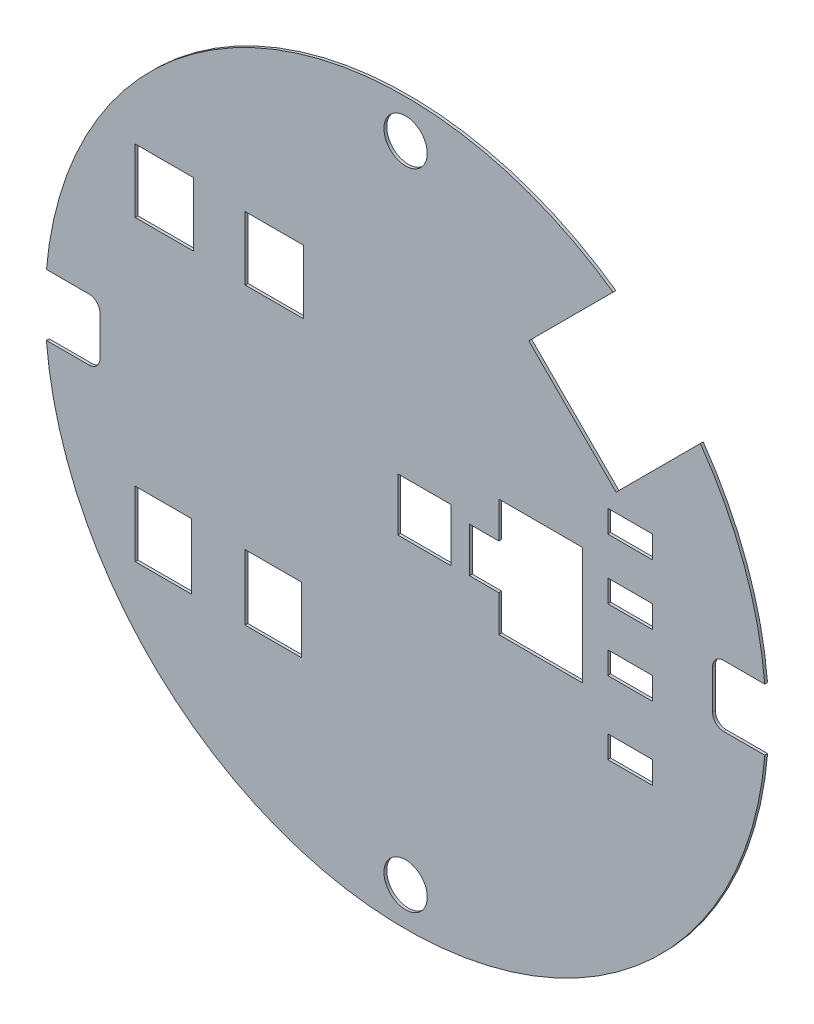
SolidWorks part; units mm, degrees
material "EPDM"
ref_plane "前视基准面" through (0, 0, 0) normal (0, 0, 1) x (1, 0, 0)
ref_plane "上视基准面" through (0, 0, 0) normal (0, 1, 0) x (1, 0, 0)
ref_plane "右视基准面" through (0, 0, 0) normal (1, 0, 0) x (0, 0, -1)
ref_plane "基准面1" through (0, 0, -54.804) normal (0, 0, -1) x (-1, 0, 0)
sketch "草图1" plane through (0, 0, -54.804) normal (0, 0, -1) x (-1, 0, 0)
  circle A0 centre (24.6985, -1.5122) radius 25.8011
  circle A1 centre (24.6985, 21.5378) radius 1.55
  circle A2 centre (24.6985, -24.5622) radius 1.55
extrude "凸台-拉伸1" add sketch "草图1" along normal blind 0.2 from surface
sketch "草图2" plane through (0, 0, -54.804) normal (0, 0, -1) x (-1, 0, 0)
  line L0 (21.4655, 0.6268) -> (25.2595, 0.6268)
  line L9 (32.0065, 11.4219) -> (36.1815, 11.4219)
  line L18 (36.1815, 11.4219) -> (36.1815, 6.8659)
  line L19 (32.0065, 6.8659) -> (36.1815, 6.8659)
  line L20 (32.0065, 11.4219) -> (32.0065, 6.8659)
  line L21 (39.8805, 11.6758) -> (44.0555, 11.6758)
  line L22 (44.0555, 11.6758) -> (44.0555, 7.1198)
  line L23 (39.8805, 7.1198) -> (44.0555, 7.1198)
  line L24 (39.8805, 11.6758) -> (39.8805, 7.1198)
  line L25 (32.1335, -9.5332) -> (36.1815, -9.5332)
  line L26 (36.1815, -9.5332) -> (36.1815, -14.2162)
  line L27 (32.1335, -14.2162) -> (36.1815, -14.2162)
  line L28 (32.1335, -9.5332) -> (32.1335, -14.2162)
  line L29 (40.0075, -9.5332) -> (44.0555, -9.5332)
  line L30 (44.0555, -9.5332) -> (44.0555, -14.2162)
  line L31 (40.0075, -14.2162) -> (44.0555, -14.2162)
  line L32 (40.0075, -9.5332) -> (40.0075, -14.2162)
  line L37 (25.2595, 0.6268) -> (25.2595, -3.1672)
  line L38 (21.4655, -3.1672) -> (25.2595, -3.1672)
  line L39 (21.4655, 0.6268) -> (21.4655, -3.1672)
extrude "切除-拉伸1" cut sketch "草图2" against normal up to next from surface
sketch "草图3" plane through (0, 0, -54.804) normal (0, 0, -1) x (-1, 0, 0)
  line L4 (15.8822, 13.5563) -> (9.6314, 7.3055)
  line L5 (9.6314, 7.3055) -> (2.9964, 13.9404)
  line L6 (2.9964, 13.9404) -> (9.2472, 20.1913)
  line L7 (9.2472, 20.1913) -> (15.8822, 13.5563)
extrude "切除-拉伸2" cut sketch "草图3" against normal up to next from surface
sketch "草图4" plane through (0, 0, -54.804) normal (0, 0, -1) x (-1, 0, 0)
  line L0 (7.0304, 4.4068) -> (7.0304, 6.0068)
  line L3 (7.0304, 6.0068) -> (10.2304, 6.0068)
  line L4 (10.2304, 6.0068) -> (10.2304, 4.4068)
  line L5 (8.6304, 4.4068) -> (7.0304, 4.4068)
  line L6 (8.6304, 4.4068) -> (10.2304, 4.4068)
  line L7 (7.0304, 0.0868) -> (7.0304, 1.6868)
  line L8 (7.0304, 1.6868) -> (10.2304, 1.6868)
  line L9 (10.2304, 1.6868) -> (10.2304, 0.0868)
  line L10 (8.6304, 0.0868) -> (7.0304, 0.0868)
  line L11 (8.6304, 0.0868) -> (10.2304, 0.0868)
  line L12 (7.0304, -4.3632) -> (7.0304, -2.7632)
  line L13 (7.0304, -2.7632) -> (10.2304, -2.7632)
  line L14 (10.2304, -2.7632) -> (10.2304, -4.3632)
  line L15 (8.6304, -4.3632) -> (7.0304, -4.3632)
  line L16 (8.6304, -4.3632) -> (10.2304, -4.3632)
  line L17 (7.0304, -9.5732) -> (7.0304, -7.9732)
  line L18 (7.0304, -7.9732) -> (10.2304, -7.9732)
  line L19 (10.2304, -7.9732) -> (10.2304, -9.5732)
  line L20 (8.6304, -9.5732) -> (7.0304, -9.5732)
  line L21 (8.6304, -9.5732) -> (10.2304, -9.5732)
  dimension "D1" = 2
  dimension "D2" = 2
  dimension "D3" = 2
extrude "切除-拉伸3" cut sketch "草图4" against normal up to next from surface
sketch "草图5" plane through (0, 0, -54.804) normal (0, 0, -1) x (-1, 0, 0)
  line L1 (14.8535, 2.6759) -> (12.0535, 2.6759)
  line L5 (14.8535, -5.7241) -> (12.0535, -5.7241)
  line L6 (12.0535, -5.7241) -> (12.0535, 2.6759)
  line L7 (14.8535, 2.6759) -> (17.6535, 2.6759)
  line L8 (20.1285, -3.1241) -> (18.0285, -3.1241)
  line L10 (17.6535, 2.6759) -> (18.0285, 2.6759)
  line L11 (18.0285, 2.6759) -> (18.0285, 0.0759)
  line L12 (18.0285, -3.1241) -> (18.0285, -5.7241)
  line L13 (18.0285, 0.0759) -> (20.1285, 0.0759)
  line L14 (20.1285, 0.0759) -> (20.1285, -3.1241)
  line L15 (18.0285, -5.7241) -> (14.8535, -5.7241)
extrude "切除-拉伸4" cut sketch "草图5" against normal up to next from surface
sketch "草图7" plane through (0, 0, -54.804) normal (0, 0, -1) x (-1, 0, 0)
  line L7 (50.9596, -3.6791) -> (50.3113, -3.6791)
  line L8 (50.9596, 0.7209) -> (50.9596, -3.6791)
  line L9 (50.3057, 0.7209) -> (50.9596, 0.7209)
  line L10 (50.3113, -3.6791) -> (47.3689, -3.6791)
  line L11 (46.569, -0.079) -> (46.5689, -2.879)
  line L12 (50.3057, 0.7209) -> (47.369, 0.7209)
  line L13 (-1.0051, 0.7209) -> (1.9316, 0.7209)
  line L14 (2.7316, -0.079) -> (2.7317, -2.879)
  line L15 (-1.0108, -3.6791) -> (1.9317, -3.6791)
  line L16 (-1.0051, 0.7209) -> (-1.659, 0.7209)
  line L17 (-1.659, 0.7209) -> (-1.659, -3.6791)
  line L18 (-1.659, -3.6791) -> (-1.0108, -3.6791)
  arc A3 (46.5689, -2.879) -> (47.3689, -3.6791) centre (47.3689, -2.8791) ccw
  arc A4 (47.369, 0.7209) -> (46.569, -0.079) centre (47.369, -0.0791) ccw
  arc A5 (1.9316, 0.7209) -> (2.7316, -0.079) centre (1.9316, -0.0791) cw
  arc A6 (2.7317, -2.879) -> (1.9317, -3.6791) centre (1.9317, -2.8791) cw
extrude "切除-拉伸5" cut sketch "草图7" against normal up to next from surface
